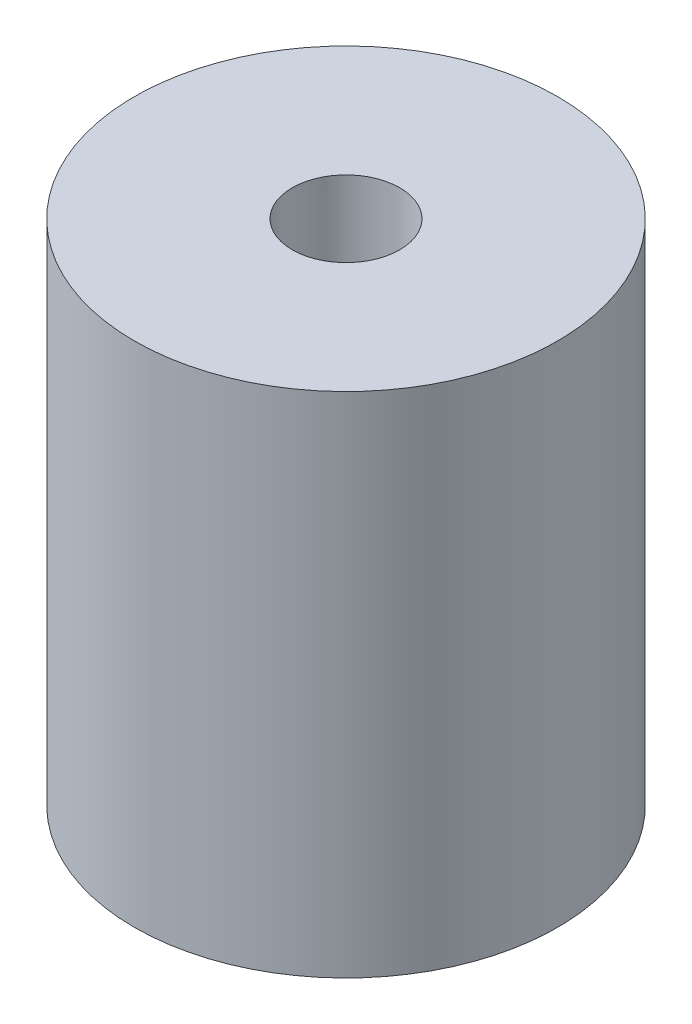
SolidWorks part; units mm, degrees
ref_plane "Front Plane" through (0, 0, 0) normal (0, 0, 1) x (1, 0, 0)
ref_plane "Top Plane" through (0, 0, 0) normal (0, 1, 0) x (1, 0, 0)
ref_plane "Right Plane" through (0, 0, 0) normal (1, 0, 0) x (0, 0, -1)
sketch "Sketch1" plane through (0, 0, 0) normal (0, 1, 0) x (1, 0, 0)
  circle A0 centre (0, 0) radius 3.175
  circle A1 centre (0, 0) radius 12.5
  dimension "D1" = 6.35
  dimension "D2" = 25
extrude "Boss-Extrude1" add sketch "Sketch1" along normal blind 30
sketch "Sketch2" plane through (0, 0, 0) normal (0, -1, 0) x (1, 0, 0)
  circle A0 centre (0, 0) radius 6.35
  dimension "D1" = 12.7
extrude "Cut-Extrude1" cut sketch "Sketch2" against normal blind 15
